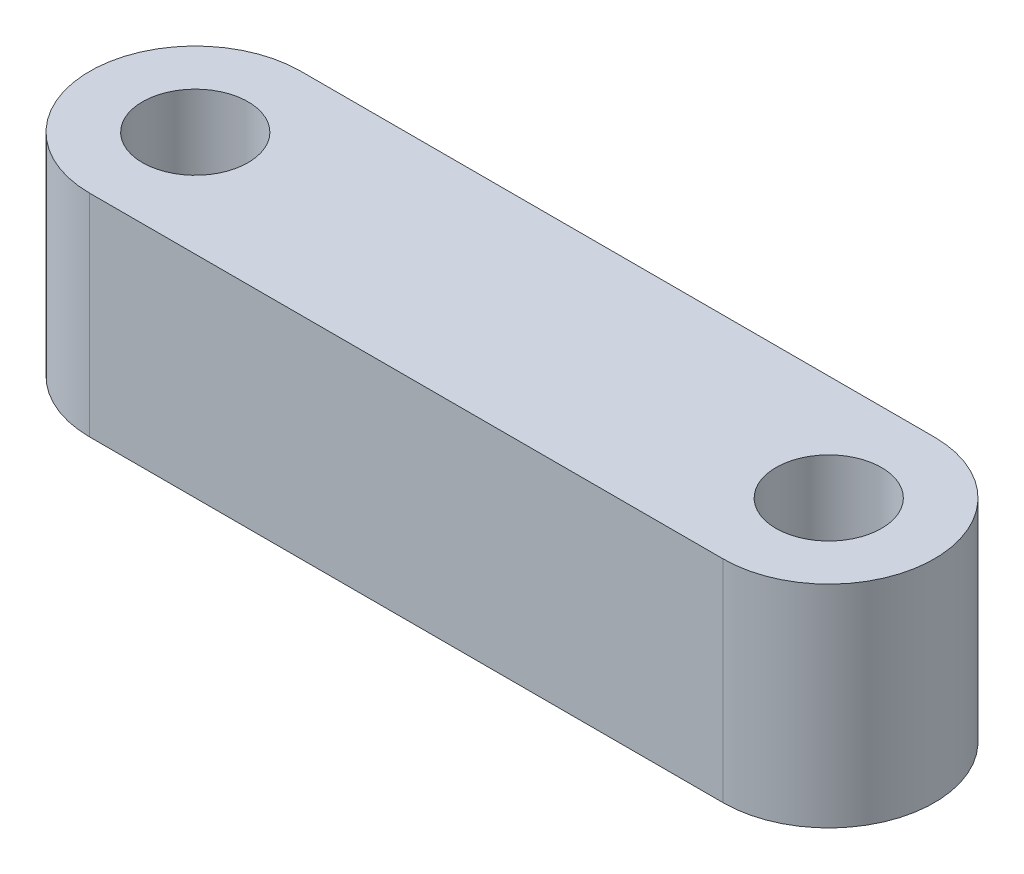
SolidWorks part; units mm, degrees
material "AISI 316 Annealed Stainless Steel Bar (SS)"
ref_plane "Front Plane" through (0, 0, 0) normal (0, 0, 1) x (1, 0, 0)
ref_plane "Top Plane" through (0, 0, 0) normal (0, 1, 0) x (1, 0, 0)
ref_plane "Right Plane" through (0, 0, 0) normal (1, 0, 0) x (0, 0, -1)
sketch "Sketch1" plane through (0, 0, 0) normal (0, 1, 0) x (1, 0, 0)
  line L0 (-15, 0) -> (15, 0) construction
  line L5 (-15, 5) -> (15, 5)
  line L6 (-15, -5) -> (15, -5)
  arc A0 (-15, 5) -> (-15, -5) centre (-15, 0) ccw
  arc A1 (15, -5) -> (15, 5) centre (15, 0) ccw
  circle A2 centre (-15, 0) radius 2.5
  circle A3 centre (15, 0) radius 2.5
  point P2 (0, 0)
  dimension "D1" = 5
  dimension "D3" = 5
  dimension "D2" = 30
extrude "Boss-Extrude1" add sketch "Sketch1" along normal blind 10
